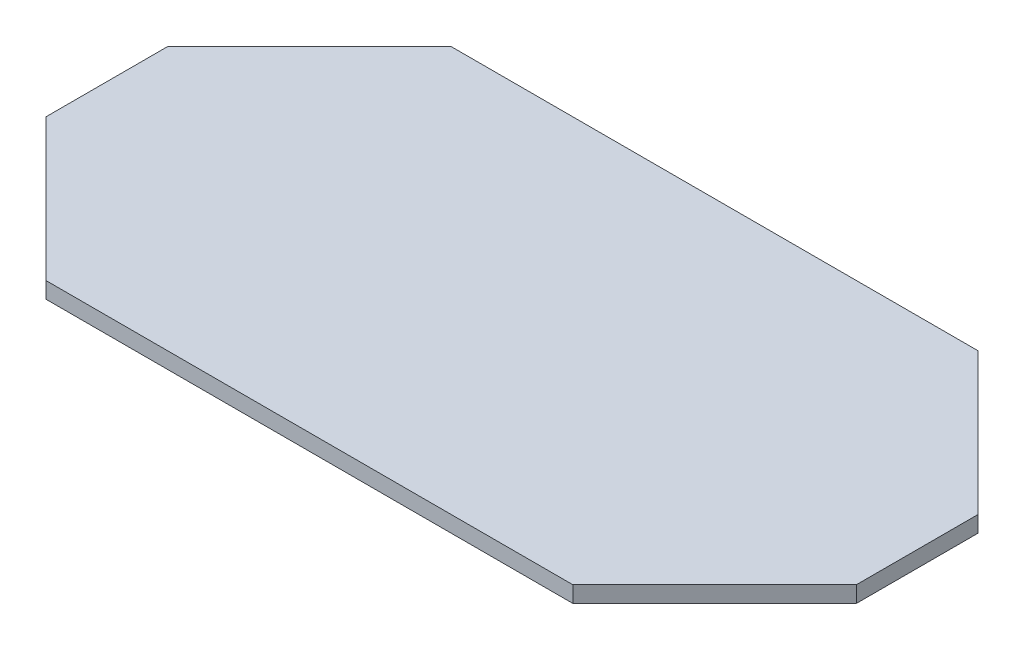
SolidWorks part; units mm, degrees
material "Polyurethane Foam Flexible"
ref_plane "Front Plane" through (0, 0, 0) normal (0, 0, 1) x (1, 0, 0)
ref_plane "Top Plane" through (0, 0, 0) normal (0, 1, 0) x (1, 0, 0)
ref_plane "Right Plane" through (0, 0, 0) normal (1, 0, 0) x (0, 0, -1)
sketch "Sketch1" plane through (0, 0, 0) normal (0, 1, 0) x (1, 0, 0)
  line L0 (-63.5, 31.75) -> (63.5, -31.75) construction
  line L1 (-63.5, 31.75) -> (63.5, 31.75)
  line L2 (-63.5, 31.75) -> (-63.5, -31.75)
  line L3 (-63.5, -31.75) -> (63.5, -31.75)
  line L4 (63.5, 31.75) -> (63.5, -31.75)
  dimension "D1" = 63.5
  dimension "D2" = 127
extrude "Boss-Extrude1" add sketch "Sketch1" along normal blind 2.54
chamfer "Chamfer1" distance 22.225 angle 45 4 edges at (63.5, 1.27, 31.75) (63.5, 1.27, -31.75) (-63.5, 1.27, 31.75) (-63.5, 1.27, -31.75)
